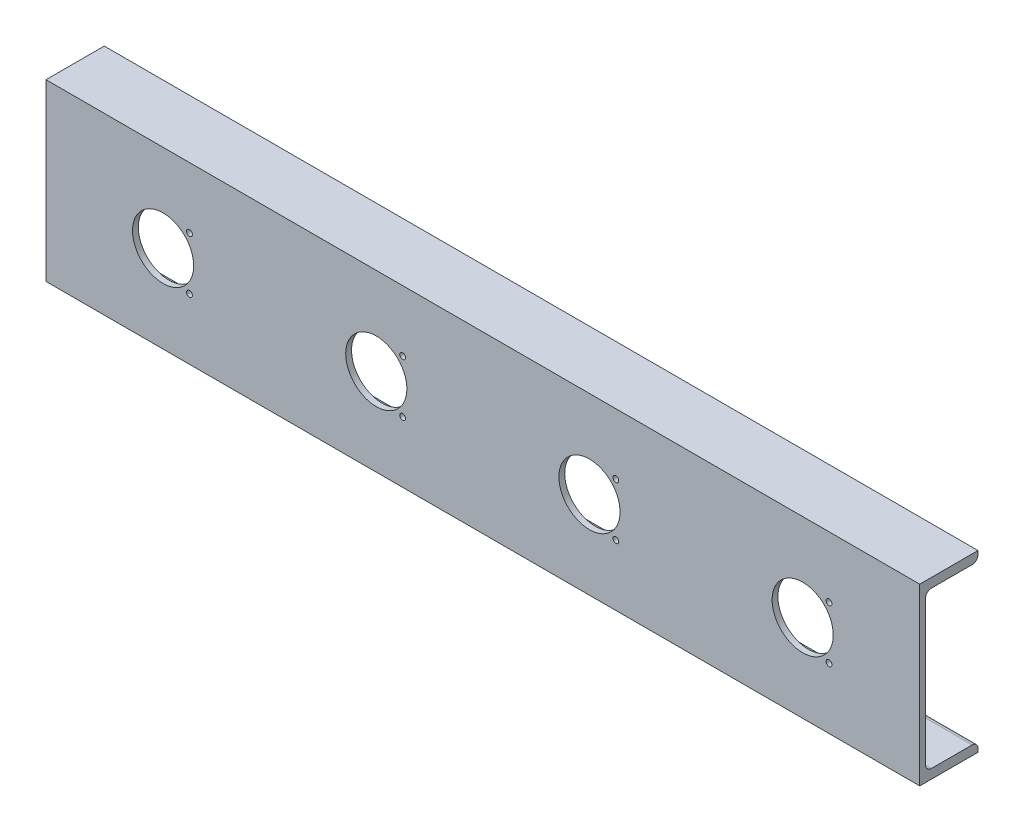
SolidWorks part; units mm, degrees
material "ASTM A36 Steel"
ref_plane "Front Plane" through (0, 0, 0) normal (0, 0, 1) x (1, 0, 0)
ref_plane "Top Plane" through (0, 0, 0) normal (0, 1, 0) x (1, 0, 0)
ref_plane "Right Plane" through (0, 0, 0) normal (1, 0, 0) x (0, 0, -1)
sketch "Sketch1" plane through (0, 0, 0) normal (1, 0, 0) x (0, 0, -1)
  line L0 (-86.6221, 113.8796) -> (-186.6221, 113.8796)
  line L1 (-186.6221, 113.8796) -> (-186.6221, -186.1204)
  line L2 (-186.6221, -186.1204) -> (-86.6221, -186.1204)
  line L3 (-86.6221, -186.1204) -> (-86.6221, -180.1204)
  line L4 (-96.6221, -170.1204) -> (-166.6221, -170.1204)
  line L5 (-176.6221, -160.1204) -> (-176.6221, 87.8796)
  line L6 (-166.6221, 97.8796) -> (-96.6221, 97.8796)
  line L7 (-86.6221, 107.8796) -> (-86.6221, 113.8796)
  arc A0 (-166.6221, -170.1204) -> (-176.6221, -160.1204) centre (-166.6221, -160.1204) cw
  arc A1 (-86.6221, -180.1204) -> (-96.6221, -170.1204) centre (-96.6221, -180.1204) ccw
  arc A2 (-96.6221, 97.8796) -> (-86.6221, 107.8796) centre (-96.6221, 107.8796) ccw
  arc A3 (-176.6221, 87.8796) -> (-166.6221, 97.8796) centre (-166.6221, 87.8796) cw
  point P12 (-86.6221, -170.1204)
  point P15 (-86.6221, 97.8796)
  dimension "D7" = 10
  dimension "D1" = 300
  dimension "D2" = 100
  dimension "D3" = 100
  dimension "D4" = 10
  dimension "D5" = 16
  dimension "D6" = 16
extrude "Boss-Extrude1" add sketch "Sketch1" along normal blind 1500
ref_plane "Plane1" through (650, 0, 0) normal (1, 0, 0) x (0, 0, -1)
sketch "Sketch5" plane through (0, 0, 176.6221) normal (0, 0, -1) x (-1, 0, 0)
  line L0 (-1500, -160.1204) -> (-1500, 87.8796) construction
  line L1 (-1500, 113.8796) -> (0, 113.8796) construction
  circle A0 centre (-1299, -36.1204) radius 52.5
  dimension "D1" = 105
  dimension "D2" = 201
  dimension "D3" = 150
extrude "Cut-Extrude3" cut sketch "Sketch5" against normal blind 30
pattern_linear "LPattern2" count 4 spacing 366 along (-1, 0, 0) of "Cut-Extrude3"
sketch "Sketch6" plane through (0, 0, 186.6221) normal (0, 0, 1) x (1, 0, 0)
  circle A1 centre (1344.2548, 9.1344) radius 5
  circle A3 centre (1344.2548, -81.3752) radius 5
  dimension "D2" = 10
  dimension "10" = 10
extrude "Cut-Extrude4" cut sketch "Sketch6" against normal through all both and the other way through all
pattern_linear "LPattern3" count 4 spacing 366 along (-1, 0, 0) of "Cut-Extrude4"
